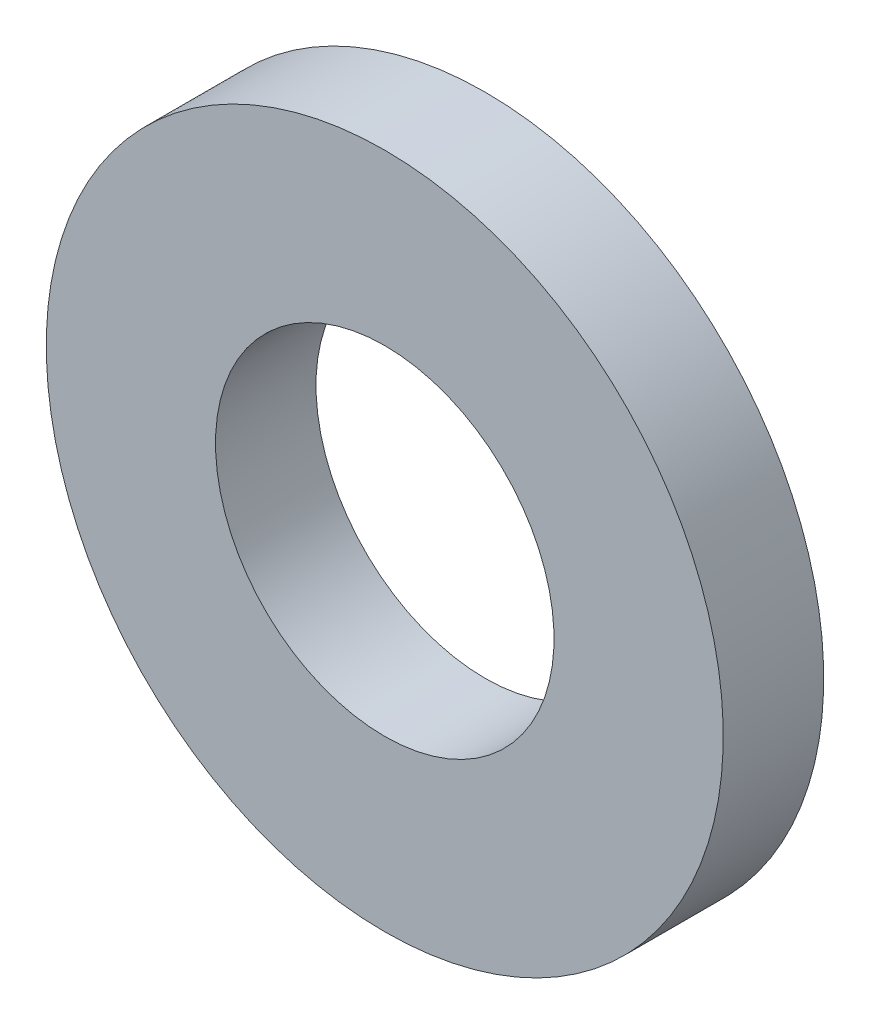
SolidWorks part; units mm, degrees
material "AISI 304"
ref_plane "Front Plane" through (0, 0, 0) normal (0, 0, 1) x (1, 0, 0)
ref_plane "Top Plane" through (0, 0, 0) normal (0, 1, 0) x (1, 0, 0)
ref_plane "Right Plane" through (0, 0, 0) normal (1, 0, 0) x (0, 0, -1)
sketch "Sketch2" plane through (0, 0, 0) normal (1, 0, 0) x (0, 0, -1)
  line L0 (-1.651, 0) -> (-4.4323, 0) construction
  line L1 (-1.651, 5.5626) -> (0, 5.5626)
  line L2 (-1.651, 5.5626) -> (-1.651, 2.7813)
  line L3 (-1.651, 2.7813) -> (0, 2.7813)
  line L4 (0, 5.5626) -> (0, 2.7813)
  dimension "D1" = 5.5626
  dimension "D2" = 11.1252
  dimension "D3" = 1.651
revolve "Revolve1" add sketch "Sketch2" angle 360 about L0
